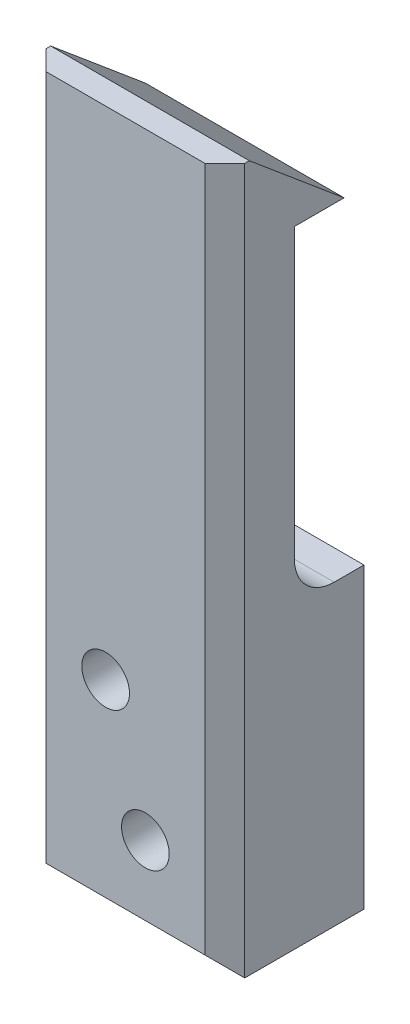
SolidWorks part; units mm, degrees
ref_plane "前视基准面" through (0, 0, 0) normal (0, 0, 1) x (1, 0, 0)
ref_plane "上视基准面" through (0, 0, 0) normal (0, 1, 0) x (1, 0, 0)
ref_plane "右视基准面" through (0, 0, 0) normal (1, 0, 0) x (0, 0, -1)
ref_plane "基准面4" through (3, 0, 0) normal (1, 0, 0) x (0, 0, -1)
sketch "草图3" plane through (3, 0, 0) normal (1, 0, 0) x (0, 0, -1)
  line L0 (0, -31) -> (-7, -31)
  line L1 (-7, -31) -> (-7, 5.5346)
  line L2 (-7, 5.5346) -> (-1, 0.5)
  line L3 (-1, 0.5) -> (-3.5, 0.5)
  line L4 (-3.5, 0.5) -> (-3.5, -14)
  line L5 (-1.5, -16) -> (0, -16)
  line L6 (0, -16) -> (0, -31)
  line L7 (144.1721, 0) -> (-3, 0) construction
  line L8 (-3, -3.5) -> (-3, 0) construction
  line L9 (-5.767, 4.5) -> (-7, 4.5)
  arc A0 (-3.5, -14) -> (-1.5, -16) centre (-1.5, -14) ccw
  dimension "D7" = 2
  dimension "D1" = 0.5
  dimension "D2" = 0.5
  dimension "D3" = 2
  dimension "D4" = 3.5
  dimension "D5" = 40
  dimension "D6" = 4
extrude "凸台-拉伸1" add sketch "草图3" against normal blind 10 contours A0 L4 L3 L2 L9 L1 L0 L6 L5
sketch "草图5" plane through (0, 0, 7) normal (0, 0, 1) x (1, 0, 0)
  point P0 (-3, -20.5)
  point P2 (-1, -26.5)
hole_wizard "M2 间隙孔1" positions "草图6" profile "草图7" hole size "M2" standard "GB" end condition through all
sketch "草图6" plane through (0, 0, 7) normal (0, 0, 1) x (1, 0, 0)
  point P0 (-1, -26.5)
  point P3 (-3, -20.5)
sketch "草图7" plane through (-1, -26.5, 7) normal (1, 0, 0) x (0, -1, 0)
  line L0 (0, 0) -> (0, 7)
  line L1 (0, 7) -> (1.2, 7)
  line L2 (1.2, 7) -> (1.2, 0)
  line L5 (1.2, 0) -> (0, 0)
  line L11 (0, -6.35) -> (0, 107.95) construction
  dimension "通孔孔直径" = 2.4
  dimension "通孔孔深度" = 7
chamfer "倒角1" distance 1 angle 45 3 edges at (-7, -13.25, 7) (3, -13.25, 7) (-2, -31, 7)
